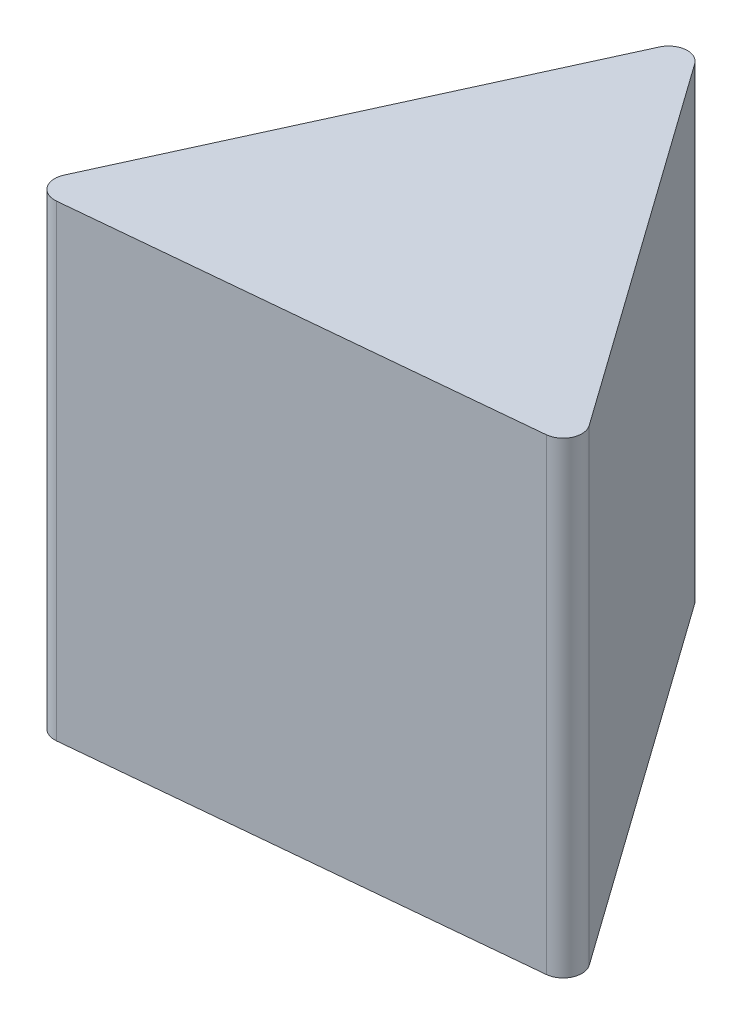
SolidWorks part; units mm, degrees
ref_plane "Front Plane" through (0, 0, 0) normal (0, 0, 1) x (1, 0, 0)
ref_plane "Top Plane" through (0, 0, 0) normal (0, 1, 0) x (1, 0, 0)
ref_plane "Right Plane" through (0, 0, 0) normal (1, 0, 0) x (0, 0, -1)
sketch "Sketch1" plane through (0, 0, 0) normal (0, 1, 0) x (1, 0, 0)
  line L1 (36.6617, -16.7539) -> (-3.8216, 40.127)
  line L2 (-3.8216, 40.127) -> (-32.8402, -23.373)
  line L3 (-32.8402, -23.373) -> (36.6617, -16.7539)
  circle A0 centre (0, 0) radius 20.1543 construction
  dimension "D1" = 63.5
extrude "Boss-Extrude1" add sketch "Sketch1" along normal blind 63.5
fillet "Fillet1" radius 2.54 3 edges at (-3.8216, 31.75, -40.127) (36.6617, 31.75, 16.7539) (-32.8402, 31.75, 23.373)
